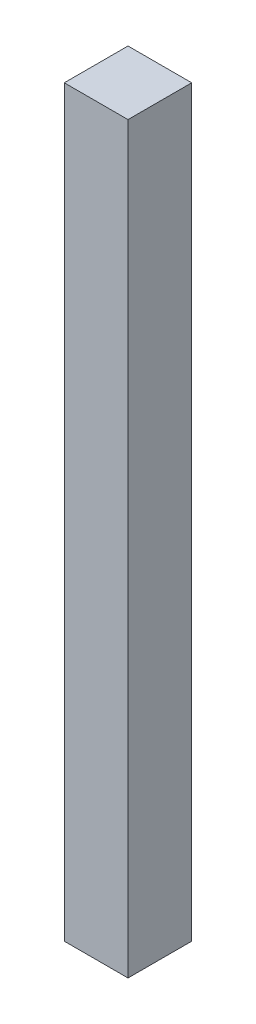
SolidWorks part; units mm, degrees
material "Alloy Steel"
ref_plane "Front Plane" through (0, 0, 0) normal (0, 0, 1) x (1, 0, 0)
ref_plane "Top Plane" through (0, 0, 0) normal (0, 1, 0) x (1, 0, 0)
ref_plane "Right Plane" through (0, 0, 0) normal (1, 0, 0) x (0, 0, -1)
sketch "Sketch1" plane through (0, 0, 0) normal (0, 1, 0) x (1, 0, 0)
  line L1 (-9.525, -9.525) -> (9.525, -9.525)
  line L2 (-9.525, -9.525) -> (-9.525, 9.525)
  line L3 (-9.525, 9.525) -> (9.525, 9.525)
  line L4 (9.525, -9.525) -> (9.525, 9.525)
  line L5 (-9.525, -9.525) -> (9.525, 9.525) construction
  line L6 (-9.525, 9.525) -> (9.525, -9.525) construction
  point P0 (0, 0)
  dimension "D1" = 19.05
  dimension "D2" = 19.05
extrude "Boss-Extrude1" add sketch "Sketch1" along normal blind 222.25
